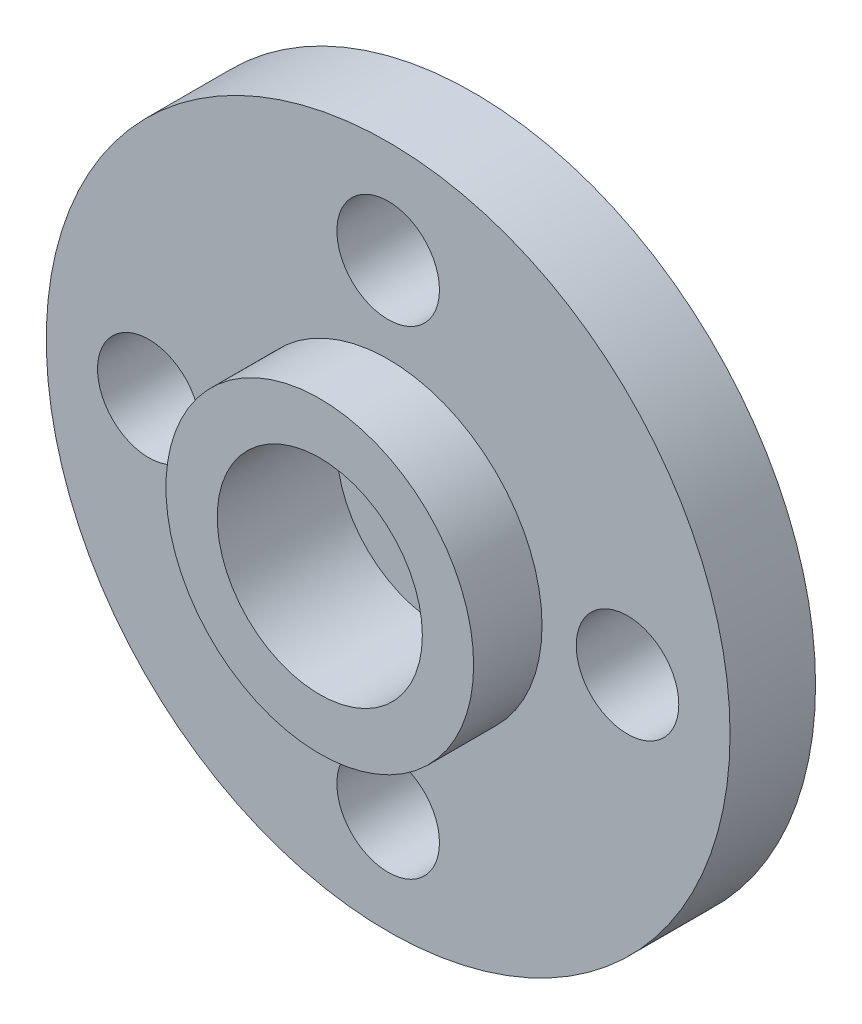
SolidWorks part; units mm, degrees
ref_plane "Спереди" through (0, 0, 0) normal (0, 0, 1) x (1, 0, 0)
ref_plane "Сверху" through (0, 0, 0) normal (0, 1, 0) x (1, 0, 0)
ref_plane "Справа" through (0, 0, 0) normal (1, 0, 0) x (0, 0, -1)
sketch "Sketch1" plane through (0, 0, 0) normal (0, 0, 1) x (1, 0, 0)
  circle A0 centre (0, 0) radius 10
  dimension "D1" = 20
extrude "Основа" add sketch "Sketch1" along normal blind 2.5
sketch "Sketch2" plane through (0, 0, 2.5) normal (0, 0, 1) x (1, 0, 0)
  circle A0 centre (0, 0) radius 4.5
  circle A1 centre (0, 0) radius 3
  dimension "D1" = 9
  dimension "D2" = 6
extrude "Выступ для оси" add sketch "Sketch2" along normal blind 2
sketch "Sketch3" plane through (0, 0, 2.5) normal (0, 0, 1) x (1, 0, 0)
  circle A0 centre (0, 0) radius 1.5
  dimension "D1" = 3
extrude "Отверстие для крепежа оси" cut sketch "Sketch3" against normal blind 13
sketch "Sketch4" plane through (0, 0, 2.5) normal (0, 0, 1) x (1, 0, 0)
  line L0 (0, 0) -> (-7, 0) construction
  line L2 (0, 0) -> (7, 0) construction
  circle A2 centre (0, 7) radius 1.5
  circle A3 centre (7, 0) radius 1.5
  circle A4 centre (0, -7) radius 1.5
  circle A5 centre (-7, 0) radius 1.5
  point P12 (0, 0)
  dimension "D1" = 4
  dimension "D2" = 3
  dimension "D3" = 7
  dimension "D4" = 7
extrude "Отверстие для крепежа" cut sketch "Sketch4" against normal blind 13
sketch "Sketch5" plane through (0, 0, 4.5) normal (0, 0, 1) x (1, 0, 0)
  circle A0 centre (0, 0) radius 3
  dimension "D1" = 6
extrude "Углубление под ось" cut sketch "Sketch5" against normal blind 3.5
